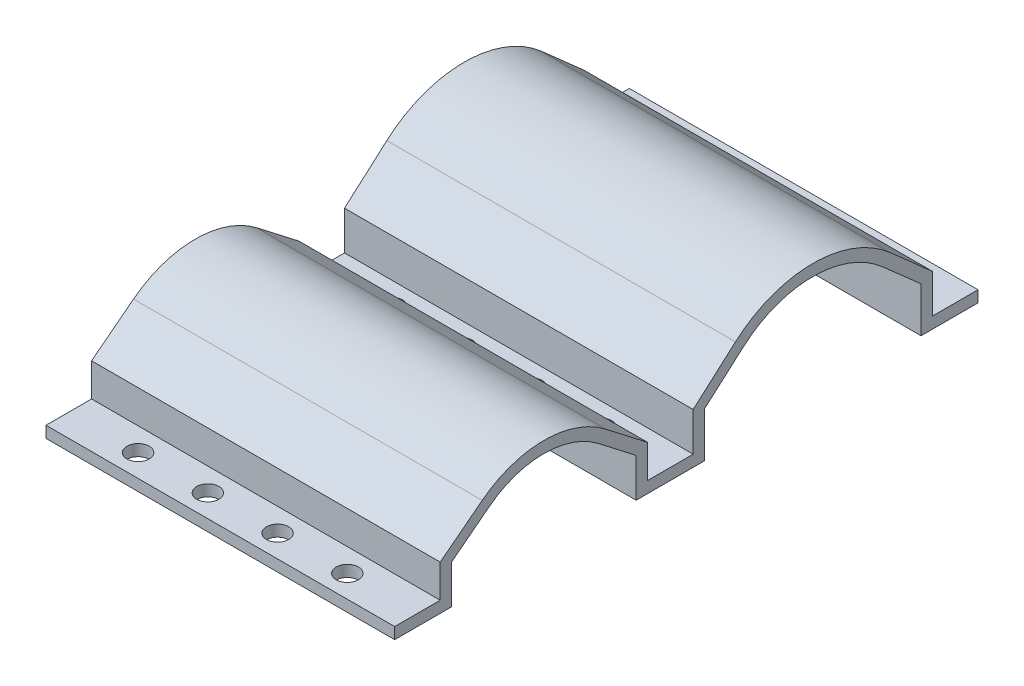
SolidWorks part; units mm, degrees
ref_plane "Front Plane" through (0, 0, 0) normal (0, 0, 1) x (1, 0, 0)
ref_plane "Top Plane" through (0, 0, 0) normal (0, 1, 0) x (1, 0, 0)
ref_plane "Right Plane" through (0, 0, 0) normal (1, 0, 0) x (0, 0, -1)
sketch "Sketch2" plane through (0, 0, 0) normal (1, 0, 0) x (0, 0, -1)
  line L0 (0, 0) -> (-10, 0)
  line L4 (-48, 0) -> (-60, 0)
  line L10 (-60, 6.8176) -> (-66.594, 11.9183)
  line L14 (-48, 7.8984) -> (-48, 0)
  line L16 (-10, 7.8984) -> (-10, 0)
  line L22 (-60, 6.8176) -> (-60, 0)
  line L27 (-41.2502, 13.863) -> (-48, 7.8984)
  line L31 (-85.806, 11.9183) -> (-92.4, 6.8176)
  line L32 (-92.4, 6.8176) -> (-92.4, 0)
  line L34 (-16.7498, 13.863) -> (-10, 7.8984)
  line L35 (-48, 0) -> (-10, 0) construction
  line L39 (-92.4, 0) -> (-60, 0) construction
  line L40 (-92.4, 0) -> (-102.4, 0)
  line L41 (0, 2) -> (-8, 2)
  line L42 (-50, 2) -> (-58, 2)
  line L43 (-58, 7.7991) -> (-58, 2)
  line L44 (-58, 7.7991) -> (-65.3703, 13.5003)
  line L45 (-87.0297, 13.5003) -> (-94.4, 7.7991)
  line L46 (-94.4, 7.7991) -> (-94.4, 2)
  line L47 (-8, 8.8001) -> (-8, 2)
  line L48 (-15.4254, 15.3617) -> (-8, 8.8001)
  line L49 (-42.5746, 15.3617) -> (-50, 8.8001)
  line L50 (-50, 8.8001) -> (-50, 2)
  line L51 (-94.4, 2) -> (-102.4, 2)
  line L52 (-102.4, 2) -> (-102.4, 0)
  line L53 (0, 2) -> (0, 0)
  line L54 (-8, 8.8001) -> (-8, 0) construction
  line L55 (0, 2) -> (-10, 2) construction
  line L56 (-48, 2) -> (-60, 2) construction
  line L57 (-50, 8.8001) -> (-50, 0) construction
  line L58 (-58, 7.7991) -> (-58, 0) construction
  line L59 (-92.4, 2) -> (-102.4, 2) construction
  line L60 (-94.4, 7.7991) -> (-94.4, 0) construction
  arc A4 (-65.3703, 13.5003) -> (-87.0297, 13.5003) centre (-76.2, -0.5) ccw
  arc A5 (-15.4254, 15.3617) -> (-42.5746, 15.3617) centre (-29, 0) ccw
  arc A8 (-16.7498, 13.863) -> (-41.2502, 13.863) centre (-29, 0) ccw
  arc A12 (-66.594, 11.9183) -> (-85.806, 11.9183) centre (-76.2, -0.5) ccw
  point P8 (-29, 18.5)
  point P9 (-76.2, 15.2)
  point P18 (-29, 0)
  point P44 (-76.2, 0)
  dimension "D3" = 15.7
  dimension "D5" = 18.5
  dimension "D1" = 18.5
  dimension "D4" = 12
  dimension "D6" = 10
  dimension "D2" = 15.2
  dimension "D7" = 32.4
  dimension "D8" = 38
  dimension "D9" = 2
extrude "Boss-Extrude1" add sketch "Sketch2" along normal blind 61.2
sketch "Sketch3" plane through (0, 2, 0) normal (0, 1, 0) x (1, 0, 0)
  line L2 (61.2, 0) -> (0, 0) construction
  line L3 (0, 0) -> (0, -8.1755) construction
  line L4 (61.2, 0) -> (61.2, -8.1755) construction
  line L5 (0, 0) -> (0, -8.1755) construction
  line L7 (0, -60) -> (0, -48) construction
  line L8 (61.2, 0) -> (0, 0) construction
  line L9 (61.2, -50) -> (0, -50) construction
  line L10 (0, -60) -> (0, -48) construction
  line L12 (61.2, -102.4) -> (0, -102.4) construction
  circle A0 centre (12.24, -3.93) radius 1.95
  circle A1 centre (24.48, -3.93) radius 1.95
  circle A2 centre (36.72, -3.93) radius 1.95
  circle A3 centre (48.96, -3.93) radius 1.95
  circle A4 centre (12.24, -53.9923) radius 1.95
  circle A5 centre (24.48, -53.9923) radius 1.95
  circle A6 centre (36.72, -53.9923) radius 1.95
  circle A7 centre (48.96, -53.9923) radius 1.95
  circle A8 centre (12.24, -98.47) radius 1.95
  circle A9 centre (24.48, -98.47) radius 1.95
  circle A10 centre (36.72, -98.47) radius 1.95
  circle A11 centre (48.96, -98.47) radius 1.95
  dimension "D1" = 3.9
  dimension "D4" = 12.24
  dimension "D5" = 12.24
  dimension "D6" = 12.24
  dimension "D3" = 12.24
  dimension "D2" = 3.93
  dimension "D9" = 3.9923
  dimension "D8" = 3.93
extrude "Cut-Extrude1" cut sketch "Sketch3" against normal up to surface (2 mm away) up to face at (30.6, 0, 54)
equation "\"MotorDIA\"= 37' Motor Diameter"
equation "\"SyringeDIA\"= 31.4'60ml Syringe Diameter"
equation "\"MotorShaftDIA\"= 6'Motor Shaft Dia"
equation "\"MotorKeyway\"= 1'Motor Shaft Keyway Depth"
equation "\"MotorLength\"= 56.7'Motor Length Excluding Shaft"
equation "\"SyringeLength\"= 117.3'60ml Syringe Length Excluding Nozzle"
equation "\"3Dtol\"= .5'Sizing Tolerance for 3D printed parts"
equation "\"ChamberDIA\"= 100 - 4'Buoyancy Chamber inner Diameter"
equation "\"ChamberThk\"= 2mm'Buoyancy Chamber Wall Thickness"
equation "\"BearingOD\"= 10"
equation "\"BearingID\"= 4"
equation "\"Bearingwidth\"= 4"
equation "\"ShaftDIA\"= 4"
equation "\"D1@Boss-Extrude1\"=\"MotorLength\"+\"3Dtol\"+4"
equation "\"D4@Sketch3\"=\"D3@Sketch3\""
equation "\"D5@Sketch3\"=\"D3@Sketch3\""
equation "\"D6@Sketch3\"=\"D3@Sketch3\""
equation "\"D3@Sketch3\"=\"D7@Sketch3\"/5"
equation "\"D3@Sketch2\"=\"SyringeDIA\"/2"
equation "\"D5@Sketch2\"=\"MotorDIA\"/2"
equation "\"D1@Sketch2\"=\"MotorDIA\"/2"
equation "\"D2@Sketch2\"=\"SyringeDIA\" / 2 - \"3Dtol\""
equation "\"D7@Sketch2\"=\"SyringeDIA\"+\"3Dtol\"*2"
equation "\"D8@Sketch2\"=\"MotorDIA\"+\"3Dtol\"*2"
